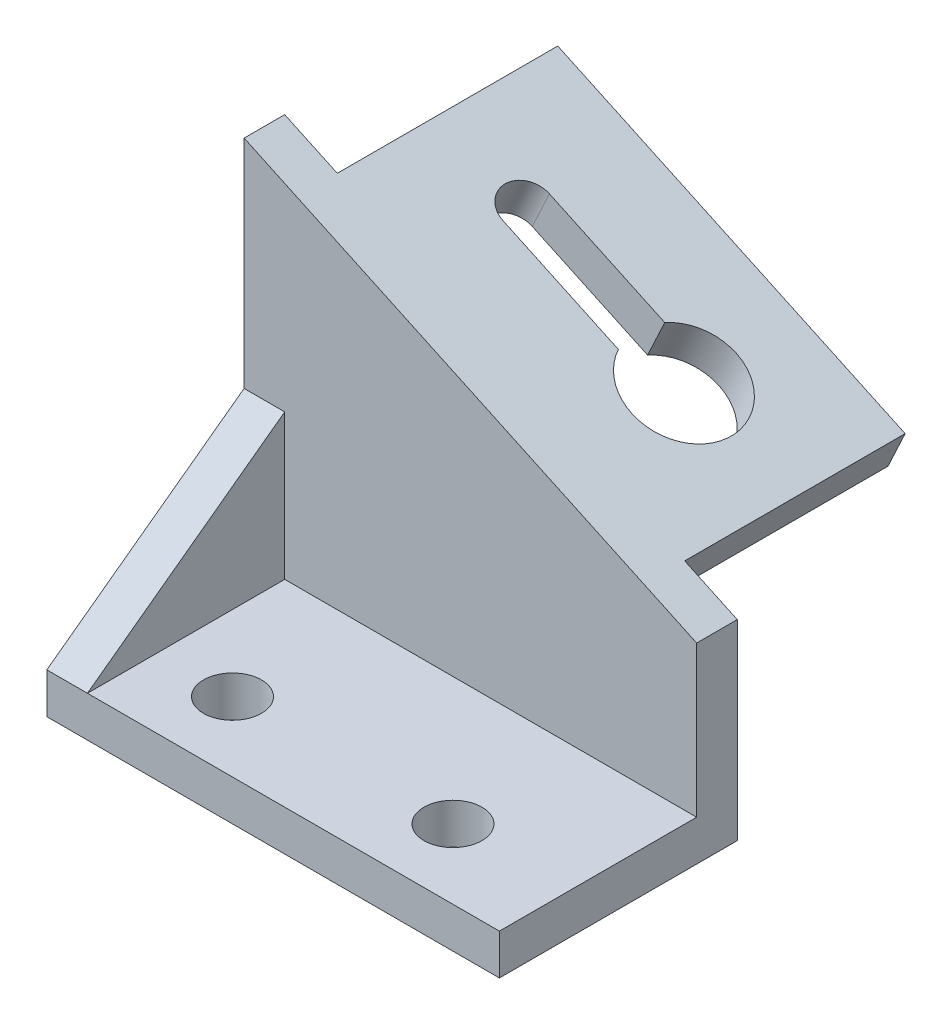
SolidWorks part; units mm, degrees
ref_plane "Front Plane" through (0, 0, 0) normal (0, 0, 1) x (1, 0, 0)
ref_plane "Top Plane" through (0, 0, 0) normal (0, 1, 0) x (1, 0, 0)
ref_plane "Right Plane" through (0, 0, 0) normal (1, 0, 0) x (0, 0, -1)
sketch "Sketch6" plane through (0, 0, 0) normal (0, 1, 0) x (1, 0, 0)
  line L1 (0, 0) -> (78, 0)
  line L2 (0, 0) -> (0, 41)
  line L3 (0, 41) -> (78, 41)
  line L4 (78, 0) -> (78, 41)
  circle A0 centre (20, 12) radius 5
  circle A1 centre (58, 12) radius 5
  point P11 (78.2993, -0.7914)
  dimension "D3" = 10
  dimension "D6" = 10
  dimension "D1" = 41
  dimension "D2" = 78
  dimension "D4" = 20
  dimension "D5" = 12
  dimension "D7" = 12
  dimension "D8" = 20
extrude "Boss-Extrude5" add sketch "Sketch6" along normal blind 7
sketch "Sketch7" plane through (0, 0, 0) normal (1, 0, 0) x (0, 0, -1)
  line L5 (0, 7) -> (34, 32)
  line L6 (34, 32) -> (34, 7)
  line L7 (0, 7) -> (41, 7) construction
  line L8 (34, 7) -> (0, 7)
  line L9 (41, 7) -> (41, 0) construction
  dimension "D1" = 25
  dimension "D2" = 7
extrude "Boss-Extrude6" add sketch "Sketch7" along normal blind 7
sketch "Sketch8" plane through (0, 0, 0) normal (0, 0, 1) x (1, 0, 0)
  line L0 (0, 0) -> (0, 69.372)
  line L1 (0, 69.372) -> (78, 33)
  line L2 (78, 33) -> (78, 0)
  line L3 (78, 0) -> (0, 0)
  dimension "D1" = 33
  dimension "D2" = 25
extrude "Boss-Extrude7" add sketch "Sketch8" along normal blind 7 from surface at -41 starting at face at (39, 3.5, -41)
sketch "Sketch9" plane through (26.571, 56.9817, 0) normal (0.4226, 0.9063, 0) x (0.9063, -0.4226, 0)
  line L0 (56.7456, 41) -> (-29.3179, 41) construction
  line L1 (-19.3179, 41) -> (46.7456, 41)
  line L2 (-19.3179, 41) -> (-19.3179, 79)
  line L3 (-19.3179, 79) -> (46.7456, 79)
  line L4 (46.7456, 41) -> (46.7456, 79)
  line L5 (18.6833, 63) -> (-3.2544, 63)
  line L6 (18.6833, 55) -> (-3.2544, 55)
  circle A0 centre (26.7456, 59) radius 9
  arc A1 (-3.2544, 63) -> (-3.2544, 55) centre (-3.2544, 59) ccw
  point P13 (0, 0)
  line M1 (56.7456, 41) -> (-29.3179, 41)
  dimension "D5" = 18
  dimension "D1" = 8
  dimension "D2" = 20
  dimension "D3" = 20
  dimension "D4" = 30
  dimension "D6" = 45
  dimension "D7" = 10
  dimension "D8" = 10
extrude "Boss-Extrude8" add sketch "Sketch9" against normal blind 7 contours L4 L3 L2 A1 L5 A0 L6 M1
